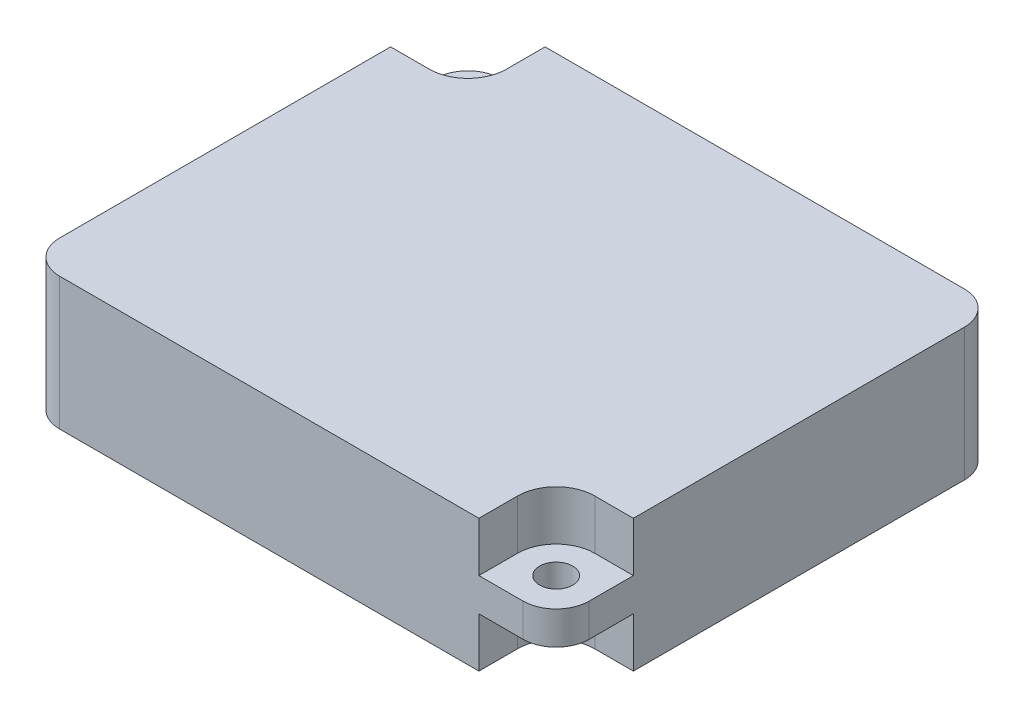
SolidWorks part; units mm, degrees
ref_plane "Front Plane" through (0, 0, 0) normal (0, 0, 1) x (1, 0, 0)
ref_plane "Top Plane" through (0, 0, 0) normal (0, 1, 0) x (1, 0, 0)
ref_plane "Right Plane" through (0, 0, 0) normal (1, 0, 0) x (0, 0, -1)
sketch "Sketch1" plane through (0, 0, 0) normal (0, 1, 0) x (1, 0, 0)
  line L1 (-24, 20) -> (24, 20)
  line L2 (-24, 20) -> (-24, -20)
  line L3 (-24, -20) -> (24, -20)
  line L4 (24, 20) -> (24, -20)
  line L5 (-24, 20) -> (24, -20) construction
  line L6 (-24, -20) -> (24, 20) construction
  point P0 (0, 0)
  dimension "D1" = 48
  dimension "D2" = 40
extrude "Boss-Extrude1" add sketch "Sketch1" along normal mid plane 12
sketch "Sketch2" plane through (0, 6, 0) normal (0, 1, 0) x (1, 0, 0)
  line L0 (-24, 13) -> (-20.5, 13)
  line L1 (-24, 20) -> (-24, -20) construction
  line L2 (-17, 16.5) -> (-17, 20)
  line L3 (24, 20) -> (-24, 20) construction
  line L4 (-17, 20) -> (-24, 20)
  line L5 (-24, 20) -> (-24, 13)
  line L6 (0, -6.6) -> (0, 6.6) construction
  line L7 (24, 20) -> (24, 13) construction
  line L8 (17, 20) -> (24, 20) construction
  line L9 (17, 16.5) -> (17, 20) construction
  line L10 (24, 13) -> (20.5, 13) construction
  line L11 (-6.6, 0) -> (6.6, 0) construction
  line L12 (24, -13) -> (20.5, -13)
  line L13 (17, -16.5) -> (17, -20)
  line L14 (17, -20) -> (24, -20)
  line L15 (24, -20) -> (24, -13)
  arc A0 (-20.5, 13) -> (-17, 16.5) centre (-20.5, 16.5) ccw
  circle A1 centre (-20.5, 16.5) radius 1.65 construction
  circle A2 centre (20.5, 16.5) radius 1.65 construction
  arc A3 (20.5, 13) -> (17, 16.5) centre (20.5, 16.5) cw construction
  circle A4 centre (20.5, -16.5) radius 1.65 construction
  arc A5 (20.5, -13) -> (17, -16.5) centre (20.5, -16.5) ccw
  dimension "D3" = 3.3
  dimension "D1" = 3.5
  dimension "D2" = 3.5
  dimension "D4" = 7
extrude "Cut-Extrude1" cut sketch "Sketch2" against normal through all both and the other way through all
sketch "Sketch3" plane through (0, 0, 0) normal (0, 1, 0) x (1, 0, 0)
  line L0 (24, -13) -> (20.5, -13) construction
  line L1 (17, -16.5) -> (17, -20) construction
  line L2 (-24, 13) -> (-20.5, 13) construction
  line L3 (-17, 16.5) -> (-17, 20) construction
  line L4 (24, -13) -> (20.5, -13)
  line L5 (17, -16.5) -> (17, -20)
  line L6 (-24, 13) -> (-20.5, 13)
  line L7 (-17, 16.5) -> (-17, 20)
  line L8 (-24, 13) -> (-24, 20)
  line L9 (-24, 20) -> (-17, 20)
  line L10 (17, -20) -> (24, -20)
  line L11 (24, -20) -> (24, -13)
  arc A0 (20.5, -13) -> (17, -16.5) centre (20.5, -16.5) ccw construction
  arc A1 (-20.5, 13) -> (-17, 16.5) centre (-20.5, 16.5) ccw construction
  arc A2 (20.5, -13) -> (17, -16.5) centre (20.5, -16.5) ccw
  arc A3 (-20.5, 13) -> (-17, 16.5) centre (-20.5, 16.5) ccw
  circle A4 centre (-20.5, 16.5) radius 1.5
  circle A5 centre (20.5, -16.5) radius 1.5
  dimension "D1" = 3
extrude "Boss-Extrude2" add sketch "Sketch3" along normal mid plane 3
fillet "Fillet1" radius 3 4 edges at (24, 0, 20) (24, 0, -20) (-24, 0, 20) (-24, 0, -20)
